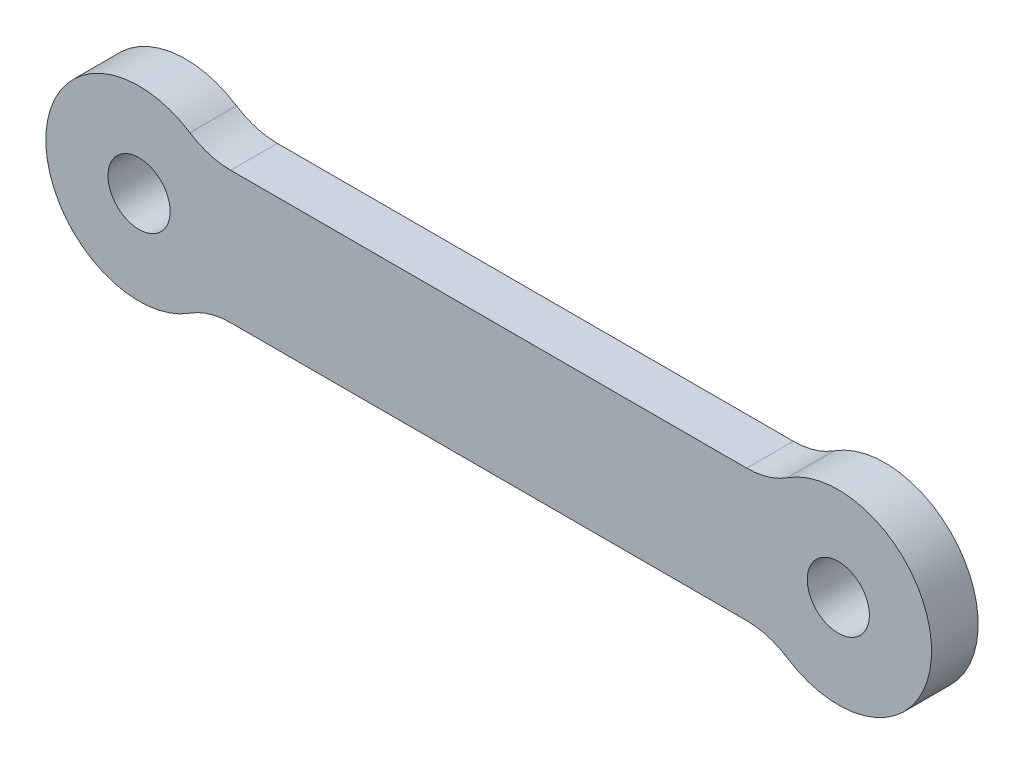
SolidWorks part; units mm, degrees
ref_plane "前视基准面" through (0, 0, 0) normal (0, 0, 1) x (1, 0, 0)
ref_plane "上视基准面" through (0, 0, 0) normal (0, 1, 0) x (1, 0, 0)
ref_plane "右视基准面" through (0, 0, 0) normal (1, 0, 0) x (0, 0, -1)
other "Configuration Table"
sketch "草图1" plane through (0, 0, 0) normal (0, 0, 1) x (1, 0, 0)
  line L0 (0, 0) -> (45, 0) construction
  line L1 (17.812, 0) -> (17.812, 4.25) construction
  line L2 (4.2353, 0) -> (4.2353, 4.25) construction
  line L3 (4.2353, 0) -> (4.2353, -4.3855) construction
  line L4 (22.5, 4.25) -> (22.5, -8.3564) construction
  line L5 (5.8984, 4.25) -> (39.1016, 4.25)
  line L6 (17.812, 0) -> (17.812, -4.25) construction
  line L7 (5.8984, 4.25) -> (5.8984, -4.25) construction
  line L8 (5.8984, -4.25) -> (39.1016, -4.25)
  circle A0 centre (0, 0) radius 2
  circle A1 centre (45, 0) radius 2
  arc A2 (3.2723, -5.0291) -> (3.2723, 5.0291) centre (0, 0) cw
  arc A3 (5.8984, 4.25) -> (3.2723, 5.0291) centre (5.8984, 9.0652) cw
  arc A4 (5.8984, -4.25) -> (3.2723, -5.0291) centre (5.8984, -9.0652) ccw
  arc A5 (39.1016, -4.25) -> (41.7277, -5.0291) centre (39.1016, -9.0652) cw
  arc A6 (41.7277, -5.0291) -> (41.7277, 5.0291) centre (45, 0) ccw
  arc A7 (39.1016, 4.25) -> (41.7277, 5.0291) centre (39.1016, 9.0652) ccw
  point P22 (22.5, -4.25)
  dimension "D1" = 4.8152
  dimension "D4" = 6
  dimension "D5" = 4
  dimension "D2" = 8.5
  dimension "D3" = 45
extrude "凸台-拉伸1" add sketch "草图1" along normal blind 3
